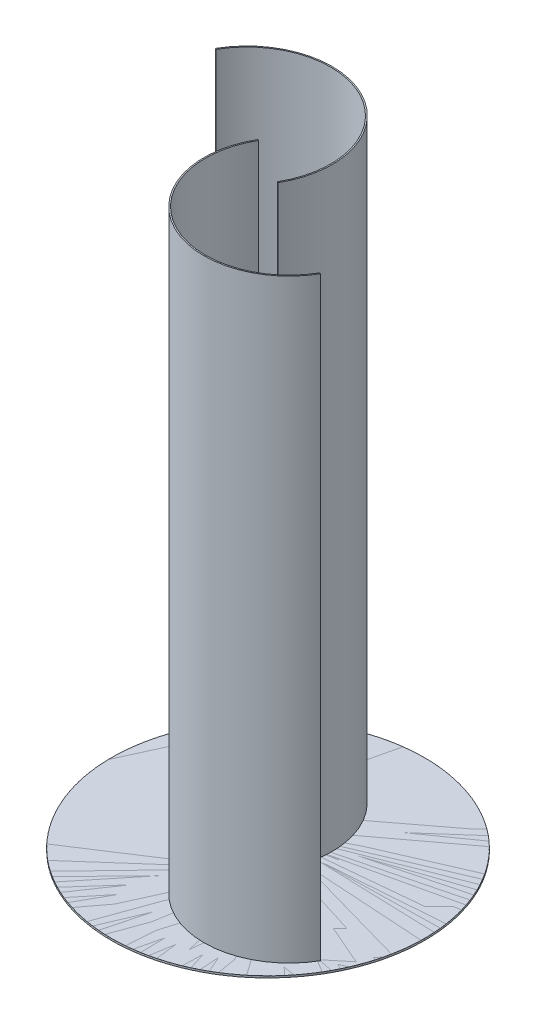
SolidWorks part; units mm, degrees
ref_plane "Alzado" through (0, 0, 0) normal (0, 0, 1) x (1, 0, 0)
ref_plane "Planta" through (0, 0, 0) normal (0, 1, 0) x (1, 0, 0)
ref_plane "Vista lateral" through (0, 0, 0) normal (1, 0, 0) x (0, 0, -1)
sketch "Croquis1" plane through (0, 0, 0) normal (0, 1, 0) x (1, 0, 0)
  circle A0 centre (0, 0) radius 250
  dimension "De" = 500
extrude "Saliente-Extruir1" add sketch "Croquis1" along normal blind 3
sketch "Croquis2" plane through (0, 3, 0) normal (0, 1, 0) x (1, 0, 0)
  line L0 (-250, 0) -> (250, 0) construction
  line L5 (-216.5064, 125) -> (216.5064, -125) construction
  line L6 (-197.69, 114.1364) -> (-195.9579, 113.1364)
  line L7 (36.1369, -20.8636) -> (37.8689, -21.8636)
  arc A0 (-196.824, 113.6364) -> (37.0029, -21.3636) centre (-79.9105, 46.1364) cw construction
  circle A8 centre (0, 0) radius 250 construction
  arc A9 (-197.69, 114.1364) -> (37.8689, -21.8636) centre (-79.9105, 46.1364) cw
  arc A10 (-195.9579, 113.1364) -> (36.1369, -20.8636) centre (-79.9105, 46.1364) cw
  circle A11 centre (0, 0) radius 227.2727 construction
  dimension "D2" = 454.5455
  dimension "d" = 135
  dimension "D1" = 30
  dimension "D4" = 2
  dimension "e" = 42.7273
extrude "Saliente-Extruir2" add sketch "Croquis2" along normal blind 950
pattern_circular "MatrizC1" count 2 over 360 about axis through (0, 0, 0) along (0, 1, 0) of bodies 102
equation "\"D2@Croquis2\"=\"De@Croquis1\"/1.1"
